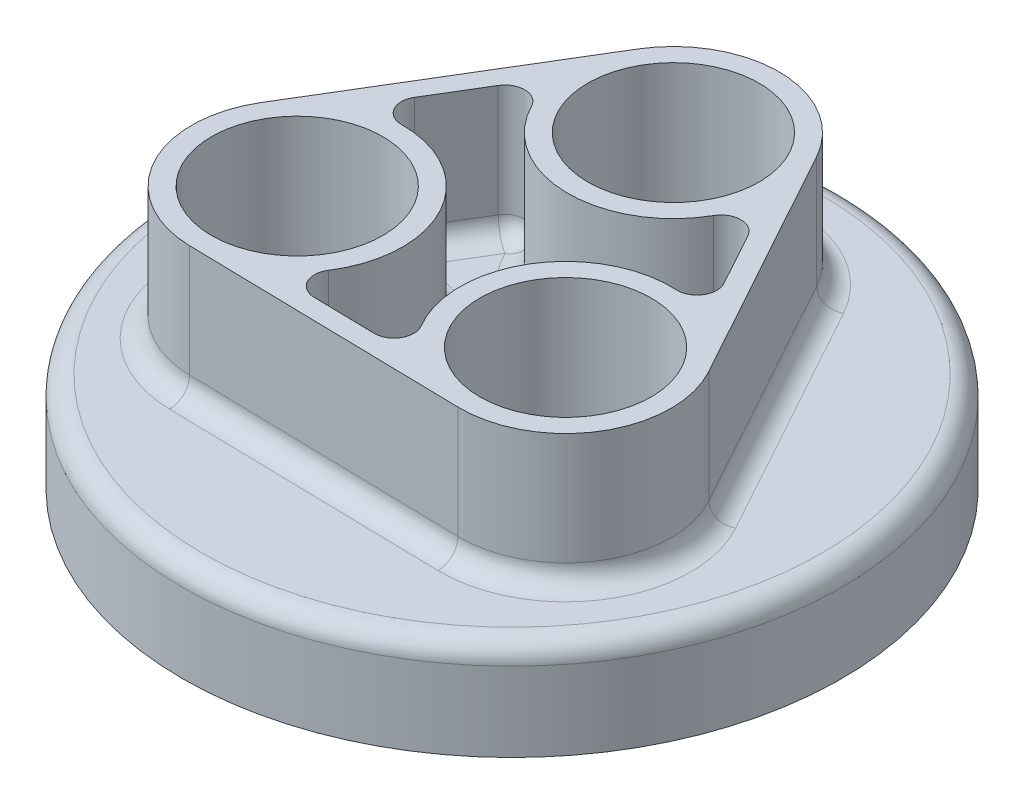
SolidWorks part; units mm, degrees
ref_plane "Front Plane" through (0, 0, 0) normal (0, 0, 1) x (1, 0, 0)
ref_plane "Top Plane" through (0, 0, 0) normal (0, 1, 0) x (1, 0, 0)
ref_plane "Right Plane" through (0, 0, 0) normal (1, 0, 0) x (0, 0, -1)
sketch "Sketch1" plane through (0, 0, 0) normal (0, 1, 0) x (1, 0, 0)
  circle A0 centre (0, 0) radius 50
  dimension "D1" = 100
extrude "Boss-Extrude1" add sketch "Sketch1" along normal blind 15
shell "Shell1" thickness 3
sketch "Sketch2" plane through (0, 15, 0) normal (0, 1, 0) x (1, 0, 0)
  line L0 (0, 0) -> (1.123, 55.206) construction
  line L1 (0, 0) -> (51.9117, -31.396) construction
  line L2 (0, 0) -> (-54.6524, -30.0884) construction
  circle A0 centre (-21.0244, -11.5748) radius 16
  circle A1 centre (0.4881, 23.995) radius 16
  circle A2 centre (20.5363, -12.4202) radius 16
  circle A3 centre (0, 0) radius 24 construction
  circle A4 centre (-21.0244, -11.5748) radius 13
  circle A5 centre (0.4881, 23.995) radius 13
  circle A6 centre (20.5363, -12.4202) radius 13
  dimension "D4" = 32
  dimension "D5" = 32
  dimension "D6" = 48
  dimension "D7" = 26
  dimension "D1" = 120
  dimension "D2" = 120
extrude "Boss-Extrude2" add sketch "Sketch2" against normal blind 15
sketch "Sketch3" plane through (0, 12, 0) normal (0, -1, 0) x (1, 0, 0)
  circle A0 centre (-21.0244, 11.5748) radius 13
  circle A1 centre (20.5363, 12.4202) radius 13
  circle A2 centre (0.4881, -23.995) radius 13
extrude "Cut-Extrude1" cut sketch "Sketch3" against normal through all
sketch "Sketch4" plane through (0, 15, 0) normal (0, 1, 0) x (1, 0, 0)
  line L0 (-34.7152, -3.2946) -> (-13.2027, 32.2752)
  line L1 (14.5044, 31.7116) -> (34.5525, -4.7037)
  line L2 (-21.3498, -27.5715) -> (20.2108, -28.4169)
  line L3 (-27.3212, 3.1341) -> (-15.4627, 22.7414)
  line L4 (16.3747, 22.0938) -> (27.426, 2.0204)
  line L5 (-11.9633, -24.7618) -> (10.9464, -25.2278)
  line L6 (-21.2888, -24.5721) -> (20.2719, -25.4175) construction
  line L7 (-32.1482, -4.8472) -> (-10.6357, 30.7227) construction
  line L8 (11.8763, 30.2647) -> (31.9245, -6.1505) construction
  arc A0 (-11.9633, -24.7618) -> (-27.3212, 3.1341) centre (-21.0244, -11.5748) ccw
  circle A1 centre (20.5363, -12.4202) radius 13
  circle A2 centre (20.5363, -12.4202) radius 13
  circle A3 centre (0.4881, 23.995) radius 13
  circle A4 centre (0.4881, 23.995) radius 13
  circle A5 centre (-21.0244, -11.5748) radius 13
  circle A6 centre (-21.0244, -11.5748) radius 13
  circle A7 centre (20.5363, -12.4202) radius 16
  arc A8 (20.2108, -28.4169) -> (34.5525, -4.7037) centre (20.5363, -12.4202) ccw
  circle A9 centre (0.4881, 23.995) radius 16
  arc A10 (14.5044, 31.7116) -> (-13.2027, 32.2752) centre (0.4881, 23.995) ccw
  circle A11 centre (-21.0244, -11.5748) radius 16
  arc A12 (-34.7152, -3.2946) -> (-21.3498, -27.5715) centre (-21.0244, -11.5748) ccw
  arc A13 (-15.4627, 22.7414) -> (16.3747, 22.0938) centre (0.4881, 23.995) ccw
  arc A14 (27.426, 2.0204) -> (10.9464, -25.2278) centre (20.5363, -12.4202) ccw
  dimension "D9" = 32
  dimension "D1" = 0
  dimension "D2" = 0
  dimension "D3" = 0
  dimension "D4" = 0
  dimension "D5" = 0
  dimension "D6" = 0
  dimension "D7" = 3
  dimension "D8" = 3
extrude "Boss-Extrude4" add sketch "Sketch4" along normal blind 20
fillet "Fillet1" radius 3 12 edges at (-21.3919, 15, -12.9377) (0.1627, 15, -7.9983) (21.9004, 15, -12.0571) (6.8454, 15, 4.1401) (-0.5084, 15, 24.9948) (-7.0081, 15, 3.8583) (-27.3212, 25, -3.1341) (-11.9633, 25, 24.7618) (27.426, 25, -2.0204) (10.9464, 25, 25.2278) (16.3747, 25, -22.0938) (-15.4627, 25, -22.7414)
fillet "Fillet2" radius 3 11 edges at (34.2271, 15, 20.7004) (24.5284, 15, -13.5039) (0.8135, 15, -39.9917) (-23.959, 15, -14.4903) (-35.0406, 15, 19.2913) (-0.5695, 15, 27.9942) (0, 15, 50) (-21.0244, 12, 27.5748) (0.4881, 12, -7.995) (20.5363, 12, 28.4202) (0, 12, 47)
